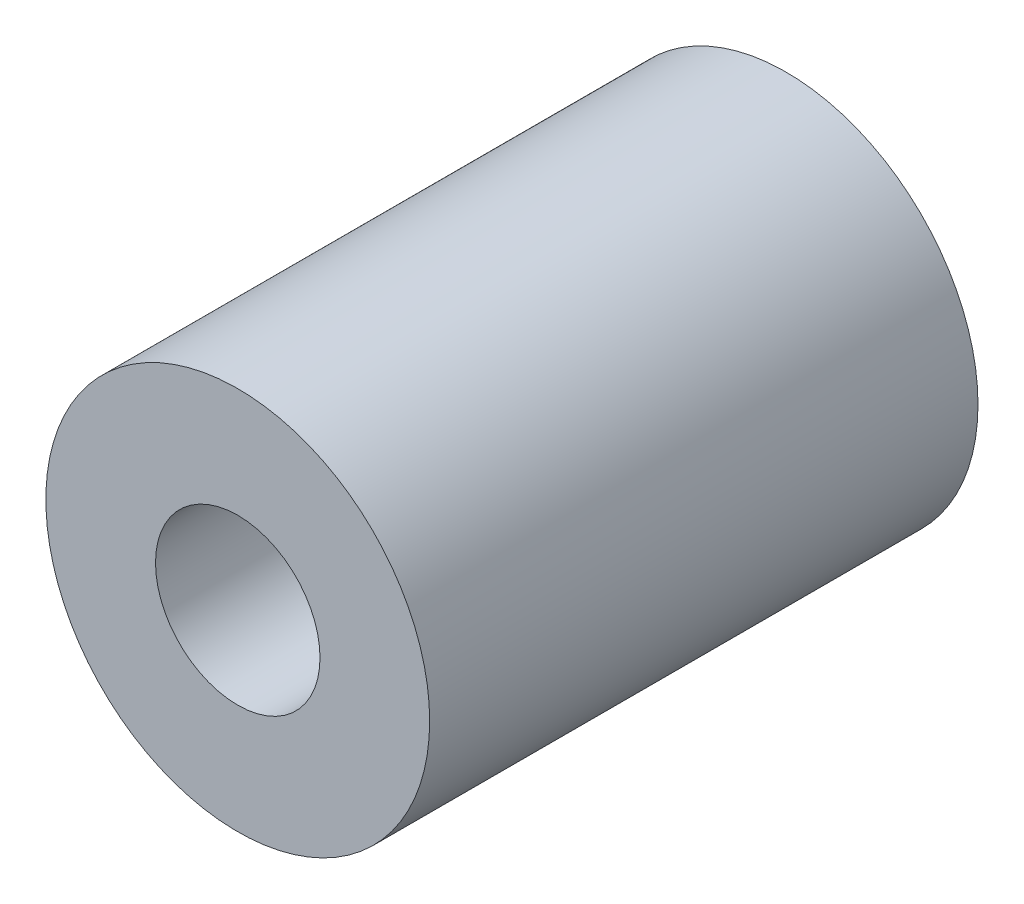
SolidWorks part; units mm, degrees
ref_plane "Front Plane" through (0, 0, 0) normal (0, 0, 1) x (1, 0, 0)
ref_plane "Top Plane" through (0, 0, 0) normal (0, 1, 0) x (1, 0, 0)
ref_plane "Right Plane" through (0, 0, 0) normal (1, 0, 0) x (0, 0, -1)
sketch "Sketch1" plane through (0, 0, 0) normal (0, 0, 1) x (1, 0, 0)
  circle A0 centre (-0.6779, 1.3381) radius 3.5
  circle A1 centre (-0.6779, 1.3381) radius 1.5
  dimension "D1" = 3
  dimension "D2" = 7
extrude "Boss-Extrude1" add sketch "Sketch1" along normal blind 10
